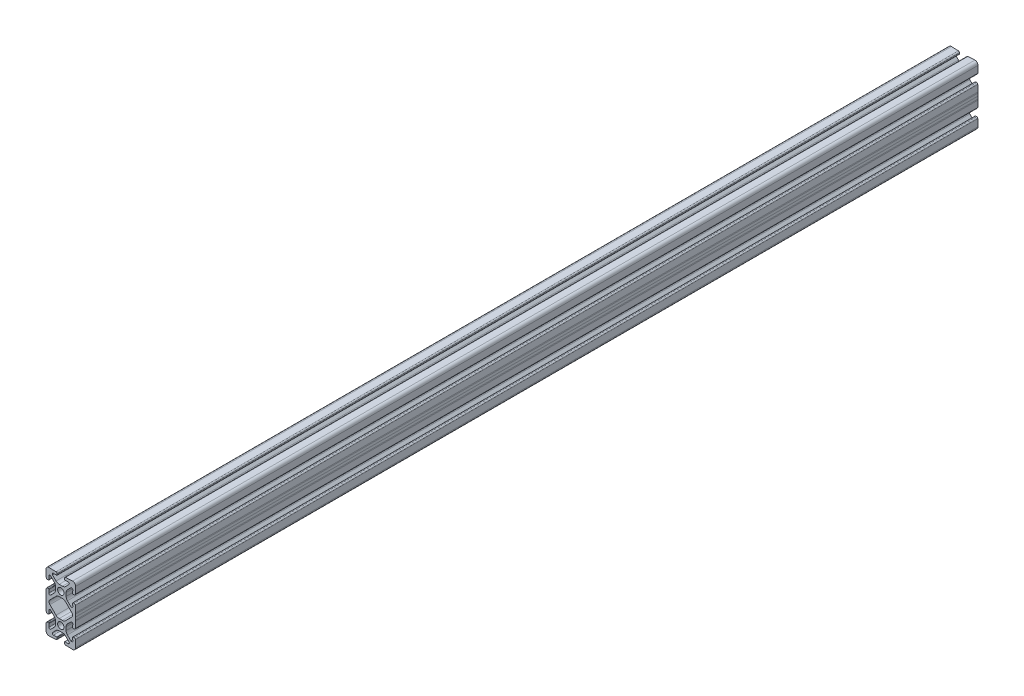
SolidWorks part; units mm, degrees
material "6063-T5"
ref_plane "Front Plane" through (0, 0, 0) normal (0, 0, 1) x (1, 0, 0)
ref_plane "Top Plane" through (0, 0, 0) normal (0, 1, 0) x (1, 0, 0)
ref_plane "Right Plane" through (0, 0, 0) normal (1, 0, 0) x (0, 0, -1)
sketch "Sketch1" plane through (0, 0, 0) normal (0, 0, 1) x (1, 0, 0)
  line L0 (0, 10) -> (0, 20) construction
  line L1 (0, 10) -> (10, 10) construction
  line L2 (0, 10) -> (-10, 20) construction
  line L3 (-7.9302, 19.9988) -> (-3.2721, 19.8361)
  line L4 (-10, 20) -> (0, 20) construction
  line L6 (-2.8352, 18.0198) -> (-4.953, 18.0937)
  line L10 (0, 13.6) -> (-1.1022, 13.6)
  line L11 (-3.2236, 14.4787) -> (-5.5244, 16.7796)
  line L24 (0, 10) -> (-10, 10) construction
  line L25 (-10, 10) -> (0, 10) construction
  line L27 (-10, 0) -> (-10, 20) construction
  line L28 (0, 20) -> (10, 20) construction
  line L29 (-2.5249, 18.3091) -> (-2.5005, 19.0087)
  line L30 (-10, -20) -> (10, -20) construction
  line L31 (0, 20) -> (0, -20) construction
  arc A0 (-9.4142, 19.4142) -> (-7.9302, 19.9988) centre (-8, 18) cw
  arc A5 (-3.2721, 19.8361) -> (-2.5005, 19.0087) centre (-3.3, 19.0366) cw
  arc A6 (-1.1022, 13.6) -> (-3.2236, 14.4787) centre (-1.1022, 16.6) cw
  circle A16 centre (0, 10) radius 2.15
  arc A18 (-5.5244, 16.7796) -> (-4.953, 18.0937) centre (-4.9799, 17.3241) cw
  arc A20 (-2.8352, 18.0198) -> (-2.5249, 18.3091) centre (-2.8247, 18.3196) ccw
  point P15 (0, -20)
  point P24 (0, 0)
  point P42 (-2.3449, 13.6)
  point P80 (-10, 10)
  dimension "D11" = 2
  dimension "D15" = 3
  dimension "Center Hole Diameter" = 4.3
  dimension "D7" = 0.8
  dimension "D8" = 0.3
  dimension "D4" = 0.7701
  dimension "D1" = 45
  dimension "D2" = 2
  dimension "Rail Width" = 20
  dimension "T-Slot Depth" = 6.4
  dimension "D9" = 1.8
  dimension "D23" = 7.2
  dimension "D5" = 11.5
  dimension "T-Slot Width" = 5
  dimension "D3" = 1.775
  dimension "D6" = 9.9598
  dimension "Rail Height" = 40
sketch "Sketch2" plane through (0, 0, 0) normal (1, 0, 0) x (0, 0, -1)
  line L0 (-304.8, 0) -> (304.8, 0)
  line L1 (-304.8, -20) -> (-304.8, 20)
  line L2 (0, 10) -> (0, 20) construction
  line L3 (0, 0) -> (0, 20) construction
  line L4 (304.8, -20) -> (304.8, 20)
  line L5 (-10, 10) -> (10, 10) construction
  point P0 (-272.3, 0)
  point P3 (0, 0)
  point P7 (272.3, 0)
  point P11 (-304.8, 0)
  point P14 (304.8, 0)
  point P23 (0, 10)
  dimension "D1" = 32.5
  dimension "Length" = 609.6
sketch "Sketch3" plane through (0, 0, 0) normal (0, 0, 1) x (1, 0, 0)
  line L0 (-2.5249, 18.3091) -> (-2.5005, 19.0087) construction
  line L1 (0, 10) -> (-10, 20) construction
  line L2 (0, 10) -> (-10, 20) construction
  line L5 (-7.9302, 19.9988) -> (-3.2721, 19.8361) construction
  line L6 (-2.8352, 18.0198) -> (-4.953, 18.0937) construction
  line L7 (-8.3091, 7.4751) -> (-9.0087, 7.4995)
  line L17 (-2.5249, 18.3091) -> (-2.5005, 19.0087)
  line L19 (-2.8352, 18.0198) -> (-4.953, 18.0937)
  line L21 (-3.6, 10) -> (0, 10) construction
  line L22 (-3.6, 8.8978) -> (-3.6, 11.1022)
  line L23 (-4.4787, 13.2236) -> (-6.7796, 15.5244)
  line L42 (-3.2236, 14.4787) -> (-5.5244, 16.7796) construction
  line L43 (0, 13.6) -> (-1.1022, 13.6) construction
  line L44 (-7.9302, 19.9988) -> (-3.2721, 19.8361)
  line L47 (-3.2236, 14.4787) -> (-5.5244, 16.7796)
  line L48 (1.1022, 13.6) -> (-1.1022, 13.6)
  line L59 (0, 13.6) -> (0, 12.15) construction
  line L60 (-9.9988, 17.9302) -> (-9.8361, 13.2721)
  line L61 (-8.0198, 12.8352) -> (-8.0937, 14.953)
  line L62 (-8.3091, 12.5249) -> (-9.0087, 12.5005)
  line L63 (-8.0198, 7.1648) -> (-8.0937, 5.047)
  line L64 (-9.9868, 2.4128) -> (-9.8361, 6.7279)
  line L65 (1.1022, 6.4) -> (-1.1022, 6.4)
  line L66 (-3.2236, 5.5213) -> (-7.3307, 1.4142)
  line L68 (-4.4787, 6.7764) -> (-6.7796, 4.4756)
  line L73 (10, 0) -> (-10, 0) construction
  line L75 (-10, 0) -> (-9.999, 1.7266)
  line L77 (10, 0) -> (9.999, 1.7266)
  line L78 (4.4787, 6.7764) -> (6.7796, 4.4756)
  line L79 (3.2236, 5.5213) -> (7.3307, 1.4142)
  line L81 (9.9868, 2.4128) -> (9.8361, 6.7279)
  line L82 (8.0198, 7.1648) -> (8.0937, 5.047)
  line L83 (8.3091, 12.5249) -> (9.0087, 12.5005)
  line L84 (8.0198, 12.8352) -> (8.0937, 14.953)
  line L85 (9.9988, 17.9302) -> (9.8361, 13.2721)
  line L87 (3.2236, 14.4787) -> (5.5244, 16.7796)
  line L88 (7.9302, 19.9988) -> (3.2721, 19.8361)
  line L89 (4.4787, 13.2236) -> (6.7796, 15.5244)
  line L90 (3.6, 8.8978) -> (3.6, 11.1022)
  line L91 (2.8352, 18.0198) -> (4.953, 18.0937)
  line L92 (2.5249, 18.3091) -> (2.5005, 19.0087)
  line L93 (8.3091, 7.4751) -> (9.0087, 7.4995)
  line L94 (-10, 0) -> (-7.9165, 0)
  line L96 (7.9165, 0) -> (10, 0)
  arc A0 (-7.9302, 19.9988) -> (-9.4142, 19.4142) centre (-8, 18) ccw construction
  arc A1 (-2.8352, 18.0198) -> (-2.5249, 18.3091) centre (-2.8247, 18.3196) ccw construction
  arc A3 (-2.8352, 18.0198) -> (-2.5249, 18.3091) centre (-2.8247, 18.3196) ccw
  arc A5 (-7.9302, 19.9988) -> (-9.9988, 17.9302) centre (-8, 18) ccw
  arc A10 (-3.2236, 5.5213) -> (-1.1022, 6.4) centre (-1.1022, 3.4) cw
  circle A13 centre (0, 10) radius 2.15 construction
  circle A14 centre (0, 10) radius 2.15
  arc A15 (-4.4787, 13.2236) -> (-3.6, 11.1022) centre (-6.6, 11.1022) cw
  arc A16 (-8.0937, 14.953) -> (-6.7796, 15.5244) centre (-7.3241, 14.9799) cw
  arc A17 (-9.0087, 12.5005) -> (-9.8361, 13.2721) centre (-9.0366, 13.3) cw
  arc A18 (-8.0198, 12.8352) -> (-8.3091, 12.5249) centre (-8.3196, 12.8247) cw
  arc A36 (-2.5005, 19.0087) -> (-3.2721, 19.8361) centre (-3.3, 19.0366) ccw construction
  arc A38 (-4.953, 18.0937) -> (-5.5244, 16.7796) centre (-4.9799, 17.3241) ccw construction
  arc A39 (-3.2236, 14.4787) -> (-1.1022, 13.6) centre (-1.1022, 16.6) ccw construction
  arc A41 (-2.5005, 19.0087) -> (-3.2721, 19.8361) centre (-3.3, 19.0366) ccw
  arc A43 (-4.953, 18.0937) -> (-5.5244, 16.7796) centre (-4.9799, 17.3241) ccw
  arc A44 (-3.2236, 14.4787) -> (-1.1022, 13.6) centre (-1.1022, 16.6) ccw
  arc A47 (-8.0198, 7.1648) -> (-8.3091, 7.4751) centre (-8.3196, 7.1753) ccw
  arc A48 (-9.0087, 7.4995) -> (-9.8361, 6.7279) centre (-9.0366, 6.7) ccw
  arc A49 (-8.0937, 5.047) -> (-6.7796, 4.4756) centre (-7.3241, 5.0201) ccw
  arc A50 (-4.4787, 6.7764) -> (-3.6, 8.8978) centre (-6.6, 8.8978) ccw
  arc A54 (-7.9165, 0) -> (-7.3307, 1.4142) centre (-5.9165, 0) cw
  arc A55 (-9.999, 1.7266) -> (-9.9868, 2.4128) centre (10.001, 1.7148) cw
  arc A56 (9.999, 1.7266) -> (9.9868, 2.4128) centre (-10.001, 1.7148) ccw
  arc A57 (7.9165, 0) -> (7.3307, 1.4142) centre (5.9165, 0) ccw
  arc A58 (4.4787, 6.7764) -> (3.6, 8.8978) centre (6.6, 8.8978) cw
  arc A59 (8.0937, 5.047) -> (6.7796, 4.4756) centre (7.3241, 5.0201) cw
  arc A60 (9.0087, 7.4995) -> (9.8361, 6.7279) centre (9.0366, 6.7) cw
  arc A61 (8.0198, 7.1648) -> (8.3091, 7.4751) centre (8.3196, 7.1753) cw
  arc A62 (3.2236, 14.4787) -> (1.1022, 13.6) centre (1.1022, 16.6) cw
  arc A63 (4.953, 18.0937) -> (5.5244, 16.7796) centre (4.9799, 17.3241) cw
  arc A64 (2.5005, 19.0087) -> (3.2721, 19.8361) centre (3.3, 19.0366) cw
  arc A65 (8.0198, 12.8352) -> (8.3091, 12.5249) centre (8.3196, 12.8247) ccw
  arc A66 (9.0087, 12.5005) -> (9.8361, 13.2721) centre (9.0366, 13.3) ccw
  arc A67 (8.0937, 14.953) -> (6.7796, 15.5244) centre (7.3241, 14.9799) ccw
  arc A68 (4.4787, 13.2236) -> (3.6, 11.1022) centre (6.6, 11.1022) ccw
  arc A70 (3.2236, 5.5213) -> (1.1022, 6.4) centre (1.1022, 3.4) ccw
  arc A71 (7.9302, 19.9988) -> (9.9988, 17.9302) centre (8, 18) cw
  arc A72 (2.8352, 18.0198) -> (2.5249, 18.3091) centre (2.8247, 18.3196) cw
  point P59 (-9.9988, 2.0698)
  point P71 (0, 0)
  point P116 (0, 6.4)
  dimension "D1" = 20
extrude "Boss-Extrude1" add sketch "Sketch3" along normal mid plane 609.6
pattern_circular "CirPattern1" count 2 over 360 about axis through (0, 0, 0) along (0, 0, 1) of "Boss-Extrude1"
ref_plane "Contact Plane 1" through (0, 20, 0) normal (0, 1, 0) x (1, 0, 0)
ref_plane "Contact Plane 2" through (10, 10, 0) normal (1, 0, 0) x (0, 0, -1)
ref_plane "Contact Plane 3" through (0, -20, 0) normal (0, -1, 0) x (-1, 0, 0)
ref_plane "Contact Plane 4" through (-10, 10, 0) normal (-1, 0, 0) x (0, 0, 1)
equation "\"D1@Sketch2\"=\"Rail Width@Sketch1\"*1.625"
equation "\"D1@Boss-Extrude1\" = \"Length@Sketch2\""
equation "\"D1@Sketch3\"=\"Rail Width@Sketch1\""
